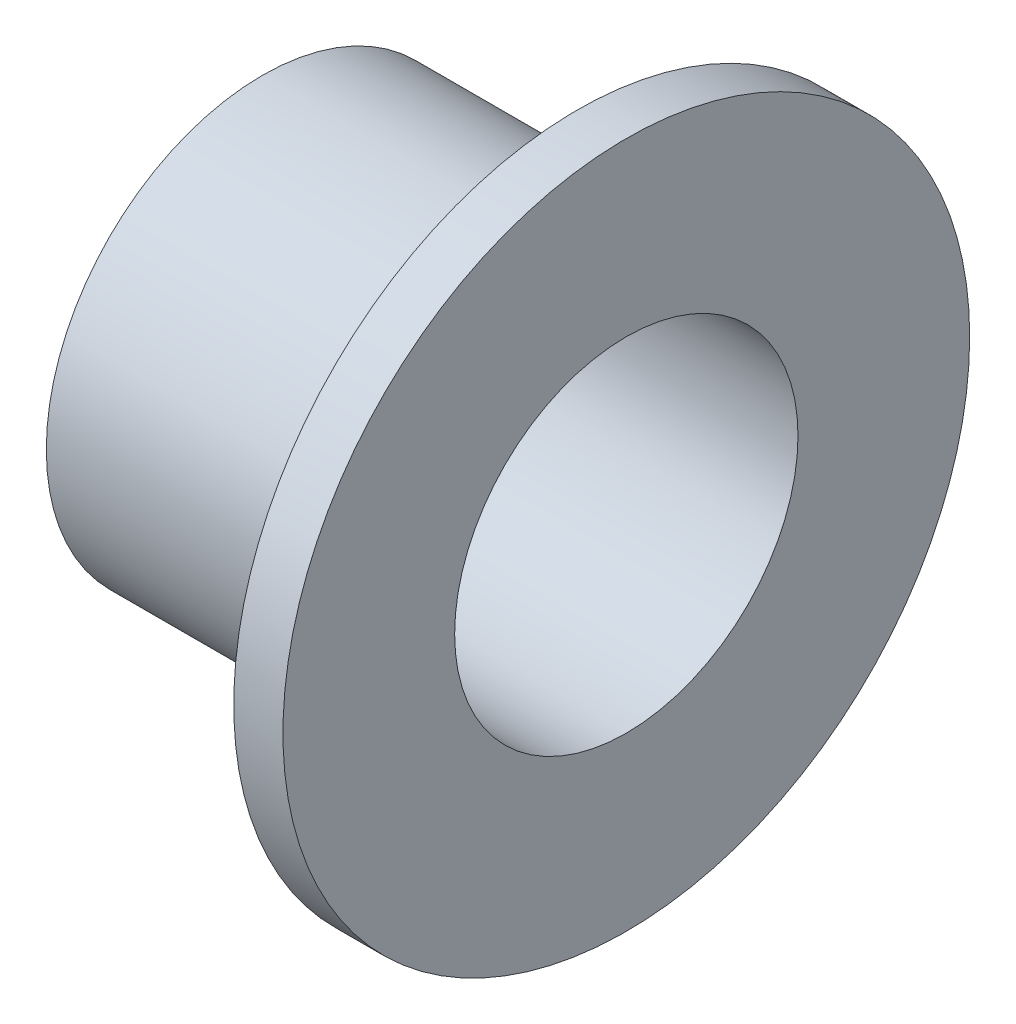
SolidWorks part; units mm, degrees
material "ABS"
ref_plane "Спереди" through (0, 0, 0) normal (0, 0, 1) x (1, 0, 0)
ref_plane "Сверху" through (0, 0, 0) normal (0, 1, 0) x (1, 0, 0)
ref_plane "Справа" through (0, 0, 0) normal (1, 0, 0) x (0, 0, -1)
sketch "Эскиз1" plane through (0, 0, 0) normal (1, 0, 0) x (0, 0, -1)
  circle A0 centre (0, 0) radius 3.775
  dimension "D1" = 7.55
extrude "Бобышка-Вытянуть1" add sketch "Эскиз1" along normal blind 5.5
sketch "Эскиз2" plane through (5.5, 0, 0) normal (1, 0, 0) x (0, 0, -1)
  circle A0 centre (0, 0) radius 6
  dimension "D1" = 12
  dimension "D2" = 0
extrude "Бобышка-Вытянуть2" add sketch "Эскиз2" along normal blind 0.86
sketch "Эскиз3" plane through (6.36, 0, 0) normal (1, 0, 0) x (0, 0, -1)
  circle A0 centre (0, 0) radius 3
  dimension "D1" = 6
extrude "Вырез-Вытянуть1" cut sketch "Эскиз3" against normal through all
